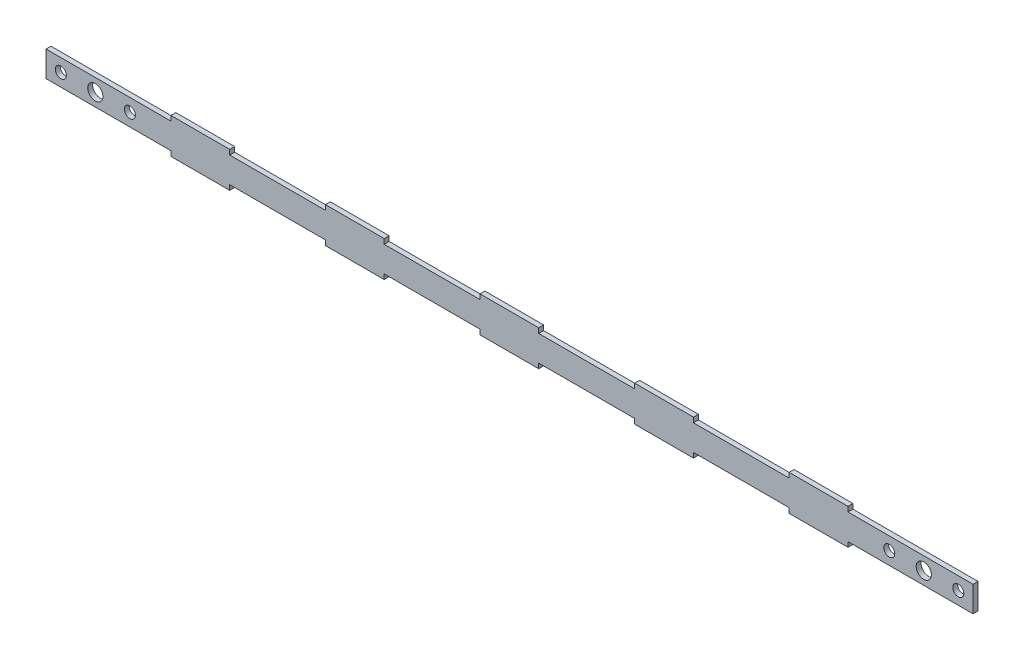
SolidWorks part; units mm, degrees
material "Acrylic (Medium-high impact)"
ref_plane "Plan de face" through (0, 0, 0) normal (0, 0, 1) x (1, 0, 0)
ref_plane "Plan de dessus" through (0, 0, 0) normal (0, 1, 0) x (1, 0, 0)
ref_plane "Plan de droite" through (0, 0, 0) normal (1, 0, 0) x (0, 0, -1)
sketch "Sketch1" plane through (0, 0, 0) normal (0, 0, 1) x (1, 0, 0)
  line L6 (298.45, -8.255) -> (-298.45, -8.255)
  line L9 (298.45, -8.255) -> (298.45, 8.255)
  line L10 (298.45, 8.255) -> (-298.45, 8.255)
  line L12 (-298.45, -8.255) -> (-298.45, 8.255)
  line L13 (298.45, -8.255) -> (-298.45, 8.255) construction
  line L14 (298.45, 8.255) -> (-298.45, -8.255) construction
  point P0 (0, 0)
  dimension "D1" = 596.9
  dimension "D2" = 16.51
extrude "Boss-Extrude1" add sketch "Sketch1" along normal blind 3.175
sketch "Sketch3" plane through (0, 8.255, 0) normal (0, 1, 0) x (1, 0, 0)
  line L5 (298.45, 0) -> (-298.45, 0) construction
  line L6 (-218.0167, 0) -> (-180.1707, 0)
  line L7 (-218.0167, 0) -> (-218.0167, -3.175)
  line L8 (-218.0167, -3.175) -> (-180.1707, -3.175)
  line L9 (-180.1707, 0) -> (-180.1707, -3.175)
  line L10 (298.45, -3.175) -> (-298.45, -3.175) construction
  line L12 (-118.5333, 0) -> (-80.6873, 0)
  line L13 (-118.5333, 0) -> (-118.5333, -3.175)
  line L14 (-118.5333, -3.175) -> (-80.6873, -3.175)
  line L15 (-80.6873, 0) -> (-80.6873, -3.175)
  line L16 (-19.05, 0) -> (18.796, 0)
  line L17 (-19.05, 0) -> (-19.05, -3.175)
  line L18 (-19.05, -3.175) -> (18.796, -3.175)
  line L19 (18.796, 0) -> (18.796, -3.175)
  line L20 (80.5603, 0) -> (118.4063, 0)
  line L21 (80.5603, 0) -> (80.5603, -3.175)
  line L22 (80.5603, -3.175) -> (118.4063, -3.175)
  line L23 (118.4063, 0) -> (118.4063, -3.175)
  line L24 (180.0437, 0) -> (217.8897, 0)
  line L25 (180.0437, 0) -> (180.0437, -3.175)
  line L26 (180.0437, -3.175) -> (217.8897, -3.175)
  line L27 (217.8897, 0) -> (217.8897, -3.175)
  point P8 (-99.6103, 0)
  point P9 (-199.0937, 0)
  point P26 (-0.127, 0)
  point P27 (99.4833, 0)
  point P31 (198.9667, 0)
  dimension "D1" = 37.846
  dimension "D2" = 99.4833
  dimension "D3" = 37.846
  dimension "D4" = 37.846
  dimension "D5" = 37.846
  dimension "D6" = 37.846
  dimension "D7" = 99.4833
  dimension "D8" = 99.4833
  dimension "D9" = 99.4833
extrude "Boss-Extrude2" add sketch "Sketch3" along normal blind 3.175
mirror "Mirror1" about plane through (0, 0, 0) normal (0, 1, 0) of "Boss-Extrude2"
sketch "Sketch4" plane through (0, 0, 0) normal (0, 0, -1) x (-1, 0, 0)
  line L0 (-298.45, -8.255) -> (-298.45, 8.255) construction
  circle A0 centre (-288.925, 0) radius 3.556
  circle A2 centre (-244.475, 0) radius 3.556
  circle A3 centre (-266.7, 0) radius 4.8895
  dimension "D4" = 7.112
  dimension "D5" = 7.112
  dimension "D6" = 9.779
  dimension "D1" = 9.525
  dimension "D2" = 31.75
  dimension "D3" = 44.45
extrude "Cut-Extrude1" cut sketch "Sketch4" against normal through all
mirror "Mirror2" about plane through (0, 0, 0) normal (1, 0, 0) of "Cut-Extrude1"
